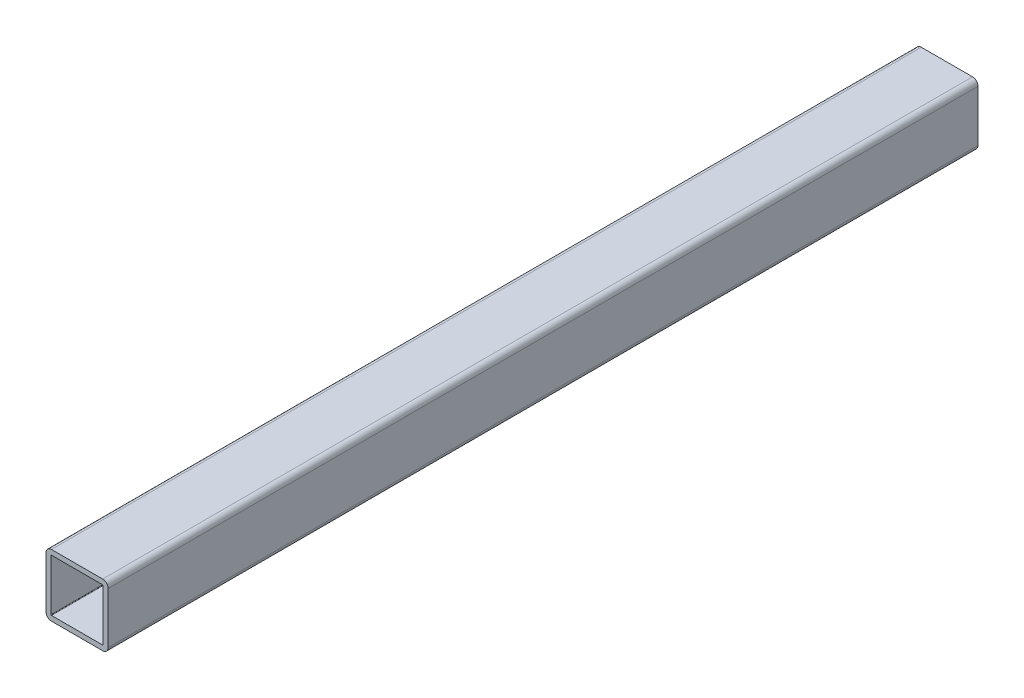
SolidWorks part; units mm, degrees
material "AISI 1020 Steel, Cold Rolled"
ref_plane "Front Plane" through (0, 0, 0) normal (0, 0, 1) x (1, 0, 0)
ref_plane "Top Plane" through (0, 0, 0) normal (0, 1, 0) x (1, 0, 0)
ref_plane "Right Plane" through (0, 0, 0) normal (1, 0, 0) x (0, 0, -1)
sketch "Sketch1" plane through (0, 0, 0) normal (0, 1, 0) x (1, 0, 0)
  line L0 (0, 0) -> (0, 350)
  dimension "D1" = 350
other "Structural Member1"
ref_plane "Plane1" through (0, 0, 0) normal (0, 0, -1) x (-1, 0, 0)
sketch "Sketch11" plane through (0, 0, 0) normal (0, 0, -1) x (-1, 0, 0)
  line L0 (-10.3, -10.5) -> (10.3, -10.5)
  line L1 (-10.5, -10.3) -> (-10.5, 10.3)
  line L2 (10.3, 10.5) -> (-10.3, 10.5)
  line L3 (10.5, 10.3) -> (10.5, -10.3)
  line L4 (-10.3, -12.5) -> (10.3, -12.5)
  line L5 (-12.5, -10.3) -> (-12.5, 10.3)
  line L6 (10.3, 12.5) -> (-10.3, 12.5)
  line L7 (12.5, 10.3) -> (12.5, -10.3)
  arc A0 (12.5, 10.3) -> (10.3, 12.5) centre (10.3, 10.3) ccw
  arc A1 (10.3, -12.5) -> (12.5, -10.3) centre (10.3, -10.3) ccw
  arc A2 (-12.5, -10.3) -> (-10.3, -12.5) centre (-10.3, -10.3) ccw
  arc A3 (-10.3, 12.5) -> (-12.5, 10.3) centre (-10.3, 10.3) ccw
  arc A4 (-10.3, 10.5) -> (-10.5, 10.3) centre (-10.3, 10.3) ccw
  arc A5 (10.5, 10.3) -> (10.3, 10.5) centre (10.3, 10.3) ccw
  arc A6 (10.3, -10.5) -> (10.5, -10.3) centre (10.3, -10.3) ccw
  arc A7 (-10.5, -10.3) -> (-10.3, -10.5) centre (-10.3, -10.3) ccw
  point P0 (-12.5, 0)
  point P1 (12.5, 0)
  point P2 (0, 12.5)
  point P3 (0, -12.5)
  point P4 (0, 0)
  point P5 (-12.5, -12.5)
  point P6 (12.5, -12.5)
  point P7 (12.5, 12.5)
  point P8 (-12.5, 12.5)
  point P33 (0, 0)
  dimension "D1" = 2.2
  dimension "Thickness" = 2
  dimension "V_leg" = 25
